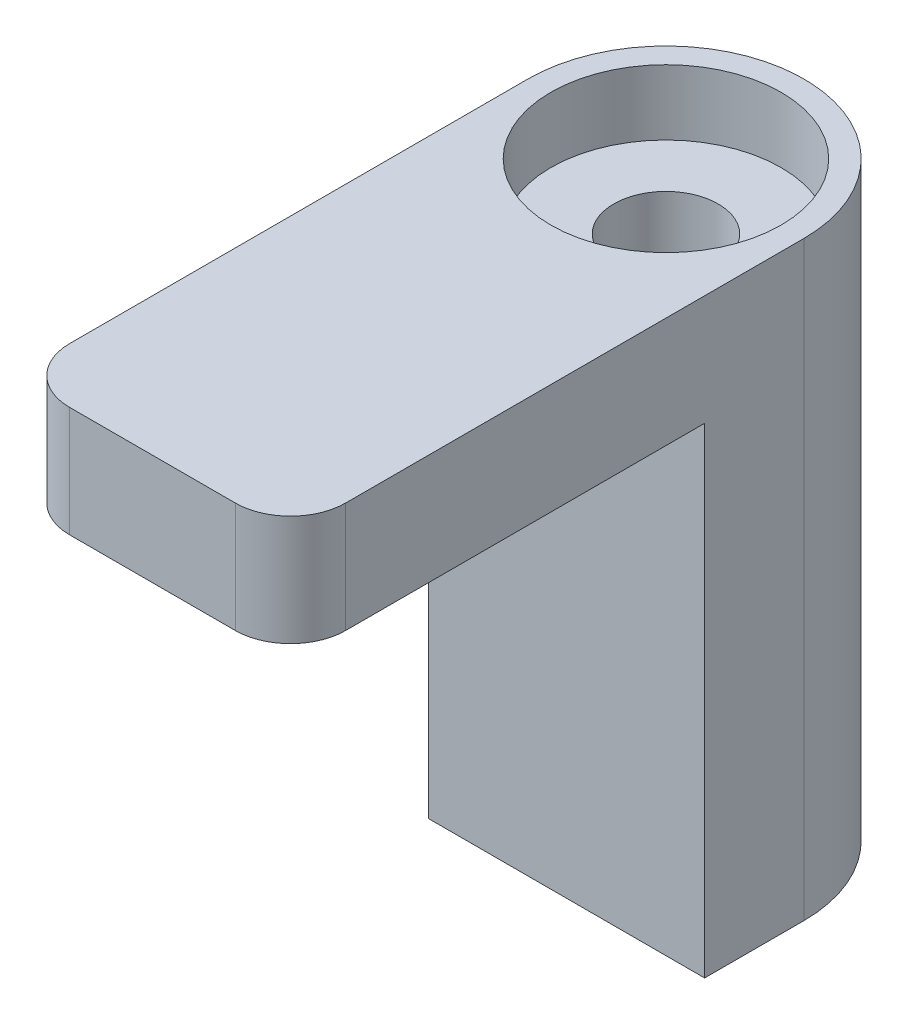
SolidWorks part; units mm, degrees
ref_plane "Front Plane" through (0, 0, 0) normal (0, 0, 1) x (1, 0, 0)
ref_plane "Top Plane" through (0, 0, 0) normal (0, 1, 0) x (1, 0, 0)
ref_plane "Right Plane" through (0, 0, 0) normal (1, 0, 0) x (0, 0, -1)
sketch "Sketch1" plane through (0, 0, 0) normal (0, 1, 0) x (1, 0, 0)
  line L1 (-6.35, 4.572) -> (6.35, 4.572) construction
  line L2 (-6.35, 4.572) -> (-6.35, 0)
  line L3 (-6.35, 0) -> (6.35, 0)
  line L4 (6.35, 4.572) -> (6.35, 0)
  line L5 (-6.35, 4.572) -> (6.35, 0) construction
  line L6 (-6.35, 0) -> (6.35, 4.572) construction
  arc A0 (6.35, 4.572) -> (-6.35, 4.572) centre (0, 4.572) ccw
  point P0 (0, 2.286)
  dimension "D1" = 12.7
  dimension "D2" = 4.572
extrude "Boss-Extrude1" add sketch "Sketch1" along normal blind 22.098
sketch "Sketch2" plane through (0, 22.098, 0) normal (0, 1, 0) x (1, 0, 0)
  line L1 (-6.35, 0) -> (6.35, 0) construction
  line L2 (-6.35, 0) -> (-6.35, -19.05)
  line L3 (6.35, 0) -> (6.35, 4.572)
  line L4 (-6.35, 4.572) -> (-6.35, 0)
  line L5 (-6.35, 0) -> (6.35, 0)
  line L6 (6.35, 0) -> (6.35, 4.572)
  line L7 (-6.35, 4.572) -> (-6.35, 0)
  line L8 (-6.35, 0) -> (6.35, 0) construction
  line L9 (-6.35, -19.05) -> (6.35, -19.05)
  line L10 (6.35, 0) -> (6.35, -19.05)
  arc A1 (6.35, 4.572) -> (-6.35, 4.572) centre (0, 4.572) ccw
  arc A2 (6.35, 4.572) -> (-6.35, 4.572) centre (0, 4.572) ccw
  dimension "D2" = 19.05
  dimension "D1" = 0
extrude "Boss-Extrude2" add sketch "Sketch2" along normal blind 5.08
fillet "Fillet1" radius 2.54 2 edges at (6.35, 24.638, 19.05) (-6.35, 24.638, 19.05)
hole_wizard "CBORE for M4 Hex Head Machine Screw1" positions "Sketch3" profile "Sketch4" counterbore size "M4" standard "ANSI Metric" end condition through all
sketch "Sketch3" plane through (0, 27.178, 0) normal (0, 1, 0) x (1, 0, 0)
  point P0 (0, 4.572)
sketch "Sketch4" plane through (0, 27.178, -4.572) normal (1, 0, 0) x (0, 0, 1)
  line L0 (0, 0) -> (0, 27.178)
  line L1 (0, 27.178) -> (2.25, 27.178)
  line L3 (2.25, 27.178) -> (2.25, 3)
  line L4 (2.25, 3) -> (5.295, 3)
  line L5 (5.295, 3) -> (5.295, 0)
  line L7 (5.295, 0) -> (0, 0)
  line L11 (0, -6.35) -> (0, 107.95) construction
  dimension "Thru Hole Dia." = 4.5
  dimension "Thru Hole Depth" = 27.178
  dimension "C'Bore Dia." = 10.59
  dimension "C'Bore Depth" = 3
hole_wizard "M4 Clearance Hole1" positions "Sketch5" profile "Sketch6" hole size "M4" standard "ANSI Metric" end condition through all
sketch "Sketch5" plane through (0, 24.178, 0) normal (0, 1, 0) x (1, 0, 0)
  point P0 (0, 4.572)
sketch "Sketch6" plane through (0, 24.178, -4.572) normal (1, 0, 0) x (0, 0, 1)
  line L0 (0, 0) -> (0, 24.178)
  line L1 (0, 24.178) -> (2.4, 24.178)
  line L2 (2.4, 24.178) -> (2.4, 0)
  line L5 (2.4, 0) -> (0, 0)
  line L11 (0, -6.35) -> (0, 107.95) construction
  dimension "Thru Hole Dia." = 4.8
  dimension "Thru Hole Depth" = 24.178
